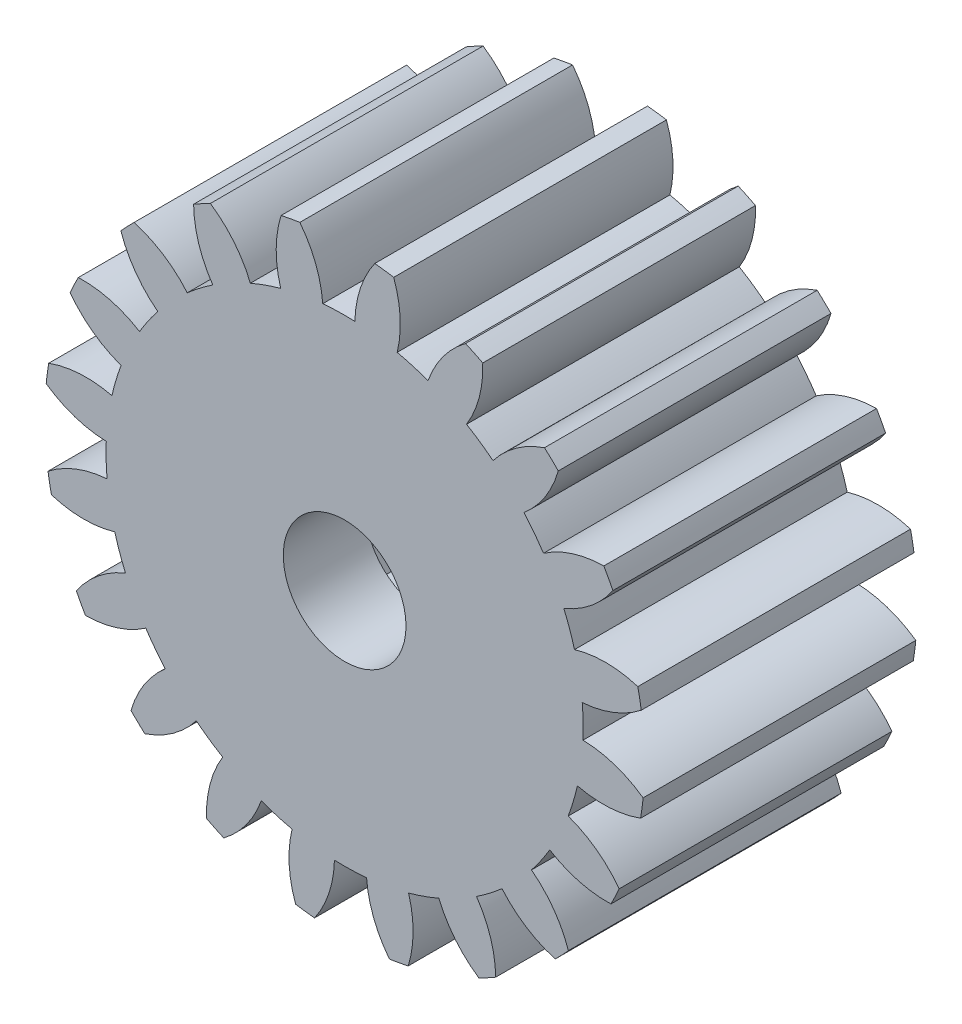
SolidWorks part; units mm, degrees
ref_plane "Front Plane" through (0, 0, 0) normal (0, 0, 1) x (1, 0, 0)
ref_plane "Top Plane" through (0, 0, 0) normal (0, 1, 0) x (1, 0, 0)
ref_plane "Right Plane" through (0, 0, 0) normal (1, 0, 0) x (0, 0, -1)
sketch "Sketch1" plane through (0, 0, 0) normal (0, 0, 1) x (1, 0, 0)
  circle A80 centre (-19.6273, -62.5489) radius 2.25
  arc A160 (-30.5716, -61.4439) -> (-28.3683, -62.1747) centre (-28.2649, -58.176) ccw
  arc A161 (-30.4792, -60.7499) -> (-30.5716, -61.4439) centre (-19.6273, -62.5489) ccw
  arc A162 (-28.1613, -60.6215) -> (-30.4792, -60.7499) centre (-29.1085, -64.5077) ccw
  arc A163 (-27.8248, -59.4919) -> (-28.1613, -60.6215) centre (-19.6273, -62.5489) ccw
  arc A164 (-29.6945, -58.116) -> (-27.8248, -59.4919) centre (-26.4908, -55.7208) ccw
  arc A165 (-29.3921, -57.4845) -> (-29.6945, -58.116) centre (-19.6273, -62.5489) ccw
  arc A166 (-27.148, -58.0787) -> (-29.3921, -57.4845) centre (-29.2498, -61.482) ccw
  arc A167 (-26.4789, -57.1083) -> (-27.148, -58.0787) centre (-19.6273, -62.5489) ccw
  arc A168 (-27.8319, -55.222) -> (-26.4789, -57.1083) centre (-24.0449, -53.9341) ccw
  arc A169 (-27.3492, -54.7149) -> (-27.8319, -55.222) centre (-19.6273, -62.5489) ccw
  arc A170 (-25.3986, -55.9734) -> (-27.3492, -54.7149) centre (-28.4491, -58.5607) ccw
  arc A171 (-24.4623, -55.2573) -> (-25.3986, -55.9734) centre (-19.6273, -62.5489) ccw
  arc A172 (-25.1662, -53.0452) -> (-24.4623, -55.2573) centre (-21.1666, -52.9906) ccw
  arc A173 (-24.5504, -52.7121) -> (-25.1662, -53.0452) centre (-19.6273, -62.5489) ccw
  arc A174 (-23.0841, -54.5118) -> (-24.5504, -52.7121) centre (-26.7849, -56.0298) ccw
  arc A175 (-21.9724, -54.1201) -> (-23.0841, -54.5118) centre (-19.6273, -62.5489) ccw
  arc A176 (-21.9583, -51.7987) -> (-21.9724, -54.1201) centre (-18.1375, -52.9827) ccw
  arc A177 (-21.2697, -51.6722) -> (-21.9583, -51.7987) centre (-19.6273, -62.5489) ccw
  arc A178 (-20.4314, -53.8369) -> (-21.2697, -51.6722) centre (-24.4201, -54.137) ccw
  arc A179 (-19.253, -53.8079) -> (-20.4314, -53.8369) centre (-19.6273, -62.5489) ccw
  arc A180 (-18.5222, -51.6046) -> (-19.253, -53.8079) centre (-15.2543, -53.9113) ccw
  arc A181 (-17.8283, -51.697) -> (-18.5222, -51.6046) centre (-19.6273, -62.5489) ccw
  arc A182 (-17.6999, -54.0149) -> (-17.8283, -51.697) centre (-21.5861, -53.0677) ccw
  arc A183 (-16.5702, -54.3514) -> (-17.6999, -54.0149) centre (-19.6273, -62.5489) ccw
  arc A184 (-15.1943, -52.4817) -> (-16.5702, -54.3514) centre (-12.7992, -55.6853) ccw
  arc A185 (-14.5629, -52.7841) -> (-15.1943, -52.4817) centre (-19.6273, -62.5489) ccw
  arc A186 (-15.157, -55.0281) -> (-14.5629, -52.7841) centre (-18.5604, -52.9264) ccw
  arc A187 (-14.1867, -55.6973) -> (-15.157, -55.0281) centre (-19.6273, -62.5489) ccw
  arc A188 (-12.3003, -54.3443) -> (-14.1867, -55.6973) centre (-11.0124, -58.1313) ccw
  arc A189 (-11.7933, -54.827) -> (-12.3003, -54.3443) centre (-19.6273, -62.5489) ccw
  arc A190 (-13.0518, -56.7776) -> (-11.7933, -54.827) centre (-15.6391, -53.727) ccw
  arc A191 (-12.3357, -57.7139) -> (-13.0518, -56.7776) centre (-19.6273, -62.5489) ccw
  arc A192 (-10.1236, -57.01) -> (-12.3357, -57.7139) centre (-10.0689, -61.0096) ccw
  arc A193 (-9.7905, -57.6257) -> (-10.1236, -57.01) centre (-19.6273, -62.5489) ccw
  arc A194 (-11.5902, -59.092) -> (-9.7905, -57.6257) centre (-13.1081, -55.3912) ccw
  arc A195 (-11.1984, -60.2037) -> (-11.5902, -59.092) centre (-19.6273, -62.5489) ccw
  arc A196 (-8.8771, -60.2179) -> (-11.1984, -60.2037) centre (-10.0611, -64.0386) ccw
  arc A197 (-8.7506, -60.9064) -> (-8.8771, -60.2179) centre (-19.6273, -62.5489) ccw
  arc A198 (-10.9153, -61.7448) -> (-8.7506, -60.9064) centre (-11.2154, -57.7561) ccw
  arc A199 (-10.8863, -62.9232) -> (-10.9153, -61.7448) centre (-19.6273, -62.5489) ccw
  arc A200 (-8.6829, -63.654) -> (-10.8863, -62.9232) centre (-10.9896, -66.9218) ccw
  arc A201 (-8.7754, -64.3479) -> (-8.6829, -63.654) centre (-19.6273, -62.5489) ccw
  arc A202 (-11.0932, -64.4763) -> (-8.7754, -64.3479) centre (-10.146, -60.5901) ccw
  arc A203 (-11.4297, -65.606) -> (-11.0932, -64.4763) centre (-19.6273, -62.5489) ccw
  arc A204 (-9.56, -66.9819) -> (-11.4297, -65.606) centre (-12.7637, -69.377) ccw
  arc A205 (-9.8624, -67.6133) -> (-9.56, -66.9819) centre (-19.6273, -62.5489) ccw
  arc A206 (-12.1065, -67.0191) -> (-9.8624, -67.6133) centre (-10.0048, -63.6158) ccw
  arc A207 (-12.7756, -67.9895) -> (-12.1065, -67.0191) centre (-19.6273, -62.5489) ccw
  arc A208 (-11.4226, -69.8758) -> (-12.7756, -67.9895) centre (-15.2096, -71.1637) ccw
  arc A209 (-11.9053, -70.3829) -> (-11.4226, -69.8758) centre (-19.6273, -62.5489) ccw
  arc A210 (-13.856, -69.1244) -> (-11.9053, -70.3829) centre (-10.8054, -66.5371) ccw
  arc A211 (-14.7922, -69.8405) -> (-13.856, -69.1244) centre (-19.6273, -62.5489) ccw
  arc A212 (-14.0883, -72.0526) -> (-14.7922, -69.8405) centre (-18.088, -72.1072) ccw
  arc A213 (-14.7041, -72.3857) -> (-14.0883, -72.0526) centre (-19.6273, -62.5489) ccw
  arc A214 (-16.1704, -70.586) -> (-14.7041, -72.3857) centre (-12.4696, -69.068) ccw
  arc A215 (-17.2821, -70.9777) -> (-16.1704, -70.586) centre (-19.6273, -62.5489) ccw
  arc A216 (-17.2962, -73.2991) -> (-17.2821, -70.9777) centre (-21.117, -72.1151) ccw
  arc A217 (-17.9848, -73.4256) -> (-17.2962, -73.2991) centre (-19.6273, -62.5489) ccw
  arc A218 (-18.8232, -71.2609) -> (-17.9848, -73.4256) centre (-14.8344, -70.9608) ccw
  arc A219 (-20.0015, -71.2899) -> (-18.8232, -71.2609) centre (-19.6273, -62.5489) ccw
  arc A220 (-20.7323, -73.4933) -> (-20.0015, -71.2899) centre (-24.0002, -71.1865) ccw
  arc A221 (-21.4263, -73.4008) -> (-20.7323, -73.4933) centre (-19.6273, -62.5489) ccw
  arc A222 (-21.5547, -71.083) -> (-21.4263, -73.4008) centre (-17.6684, -72.0301) ccw
  arc A223 (-22.6843, -70.7464) -> (-21.5547, -71.083) centre (-19.6273, -62.5489) ccw
  arc A224 (-24.0602, -72.6161) -> (-22.6843, -70.7464) centre (-26.4553, -69.4125) ccw
  arc A225 (-24.6916, -72.3137) -> (-24.0602, -72.6161) centre (-19.6273, -62.5489) ccw
  arc A226 (-24.0975, -70.0697) -> (-24.6916, -72.3137) centre (-20.6942, -72.1714) ccw
  arc A227 (-25.0679, -69.4005) -> (-24.0975, -70.0697) centre (-19.6273, -62.5489) ccw
  arc A228 (-26.9542, -70.7535) -> (-25.0679, -69.4005) centre (-28.2421, -66.9666) ccw
  arc A229 (-27.4613, -70.2708) -> (-26.9542, -70.7535) centre (-19.6273, -62.5489) ccw
  arc A230 (-26.2028, -68.3202) -> (-27.4613, -70.2708) centre (-23.6155, -71.3708) ccw
  arc A231 (-26.9189, -67.384) -> (-26.2028, -68.3202) centre (-19.6273, -62.5489) ccw
  arc A232 (-29.131, -68.0878) -> (-26.9189, -67.384) centre (-29.1856, -64.0882) ccw
  arc A233 (-29.4641, -67.4721) -> (-29.131, -68.0878) centre (-19.6273, -62.5489) ccw
  arc A234 (-27.6644, -66.0058) -> (-29.4641, -67.4721) centre (-26.1464, -69.7066) ccw
  arc A235 (-28.0561, -64.8941) -> (-27.6644, -66.0058) centre (-19.6273, -62.5489) ccw
  arc A236 (-30.3774, -64.8799) -> (-28.0561, -64.8941) centre (-29.1934, -61.0592) ccw
  arc A237 (-30.5039, -64.1914) -> (-30.3774, -64.8799) centre (-19.6273, -62.5489) ccw
  arc A238 (-28.3392, -63.353) -> (-30.5039, -64.1914) centre (-28.0391, -67.3417) ccw
  arc A239 (-28.3683, -62.1747) -> (-28.3392, -63.353) centre (-19.6273, -62.5489) ccw
extrude "Boss-Extrude1" add sketch "Sketch1" against normal blind 10
sketch "Sketch2" plane through (0, 0, -10) normal (0, 0, -1) x (-1, 0, 0)
  line L0 (24.4003, -67.5707) -> (17.6648, -69.1934) construction
  line L1 (26.3628, -60.9262) -> (24.4003, -67.5707) construction
  line L2 (21.5897, -55.9045) -> (26.3628, -60.9262) construction
  line L3 (14.8542, -57.5271) -> (21.5897, -55.9045) construction
  line L4 (17.6648, -69.1934) -> (12.8918, -64.1716) construction
  line L5 (12.8918, -64.1716) -> (14.8542, -57.5271) construction
  line L6 (24.4003, -67.5707) -> (17.6648, -69.1934)
  line L7 (26.3628, -60.9262) -> (24.4003, -67.5707)
  line L8 (21.5897, -55.9045) -> (26.3628, -60.9262)
  line L9 (14.8542, -57.5271) -> (21.5897, -55.9045)
  line L10 (17.6648, -69.1934) -> (12.8918, -64.1716)
  line L11 (12.8918, -64.1716) -> (14.8542, -57.5271)
extrude "Cut-Extrude1" cut sketch "Sketch2" against normal blind 7
